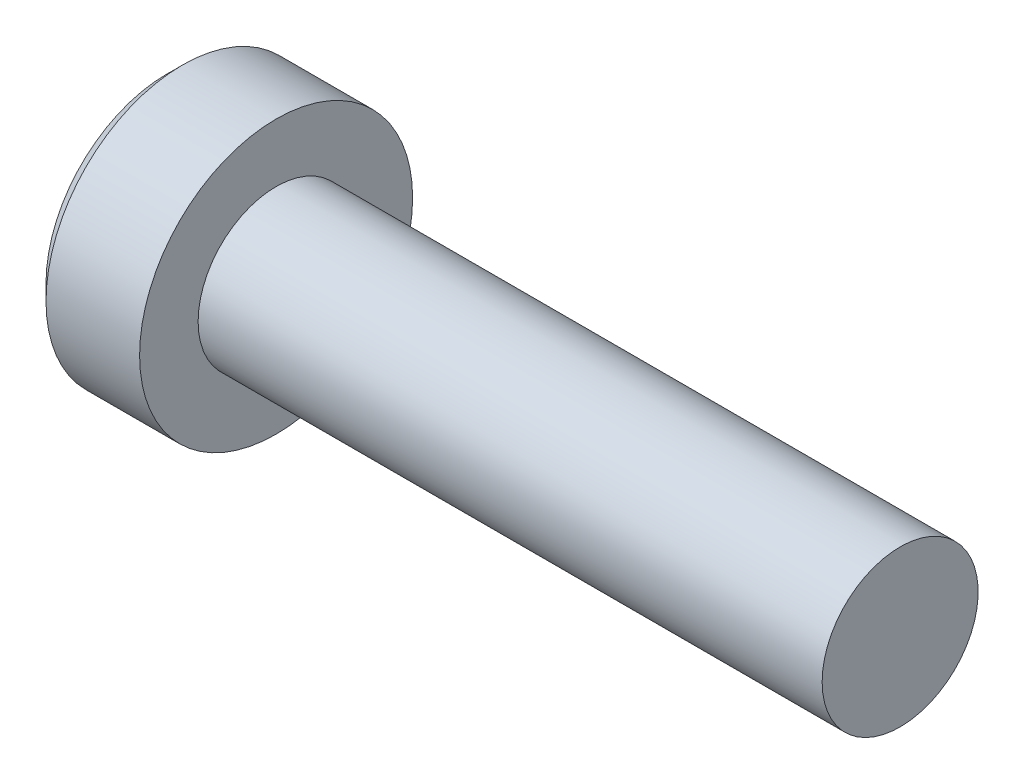
SolidWorks part; units mm, degrees
ref_plane "Front Plane" through (0, 0, 0) normal (0, 0, 1) x (1, 0, 0)
ref_plane "Top Plane" through (0, 0, 0) normal (0, 1, 0) x (1, 0, 0)
ref_plane "Right Plane" through (0, 0, 0) normal (1, 0, 0) x (0, 0, -1)
sketch "Sketch1" plane through (0, 0, 0) normal (0, 0, 1) x (1, 0, 0)
  line L0 (-2.8, 0) -> (16, 0) construction
  line L1 (16, 0) -> (16, 2)
  line L2 (16, 2) -> (0, 2)
  line L3 (0, 2) -> (0, 3.5)
  line L4 (0, 3.5) -> (-2.8, 3.5)
  line L5 (-2.8, 3.5) -> (-2.8, 0)
  line L6 (-2.8, 0) -> (16, 0)
  dimension "MSM_32" = 4
  dimension "MSM_33" = 7
  dimension "MSM_34" = 16
  dimension "MSM_35" = 2.8
revolve "Revolve1" add sketch "Sketch1" angle 360 about L0
cosmetic thread "Thread5" parameters "ATD"=3.242
sketch "Sketch2" plane through (-2.8, 0, 0) normal (-1, 0, 0) x (0, 0, 1)
  line L1 (0, 1.7321) -> (-1.5, 0.866)
  line L2 (-1.5, 0.866) -> (-1.5, -0.866)
  line L3 (-1.5, -0.866) -> (0, -1.7321)
  line L4 (0, -1.7321) -> (1.5, -0.866)
  line L5 (1.5, -0.866) -> (1.5, 0.866)
  line L6 (1.5, 0.866) -> (0, 1.7321)
  circle A0 centre (0, 0) radius 1.5 construction
  dimension "MSM_36" = 3
extrude "Cut-Extrude1" cut sketch "Sketch2" against normal blind 2
sketch "Sketch3" plane through (0, 0, 0) normal (0, 0, 1) x (1, 0, 0)
  line L0 (-0.8, 0) -> (0.066, 0) construction
  line L1 (-0.8, -0.866) -> (-0.8, 0.866) construction
  line L2 (0.066, 0) -> (-0.8, 1.5)
  line L3 (-0.8, 0.866) -> (-0.8, 1.7321) construction
  line L4 (-0.8, 1.5) -> (-0.8, 0)
  line L5 (-0.8, 0) -> (0.066, 0)
  dimension "FIX_2" = 30
  dimension "FIX_3" = 3
revolve "Cut-Revolve1" cut sketch "Sketch3" angle 360 about L0
chamfer "Chamfer1" distance 0.4 1 edges at (-2.8, 0, 3.5)
equation "\"FIX_5@Chamfer1\" = \"MSM_32@Sketch1\" / 10"
equation "\"FIX_3@Sketch3\" = \"MSM_36@Sketch2\""
